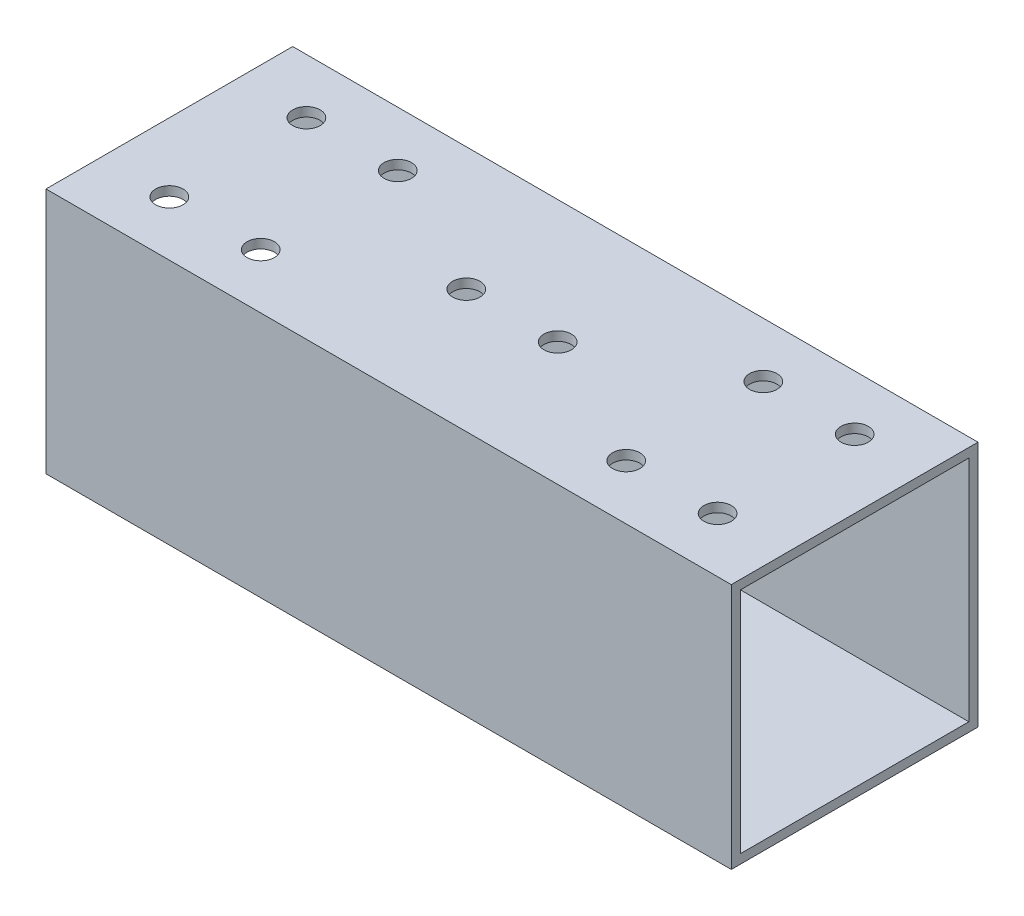
SolidWorks part; units mm, degrees
material "Plain Carbon Steel"
ref_plane "Front Plane" through (0, 0, 0) normal (0, 0, 1) x (1, 0, 0)
ref_plane "Top Plane" through (0, 0, 0) normal (0, 1, 0) x (1, 0, 0)
ref_plane "Right Plane" through (0, 0, 0) normal (1, 0, 0) x (0, 0, -1)
sketch "Sketch1" plane through (0, 0, 0) normal (1, 0, 0) x (0, 0, -1)
  line L1 (27, -27) -> (-27, -27)
  line L2 (27, -27) -> (27, 27)
  line L3 (27, 27) -> (-27, 27)
  line L4 (-27, -27) -> (-27, 27)
  line L5 (27, -27) -> (-27, 27) construction
  line L6 (27, 27) -> (-27, -27) construction
  line L11 (23.1777, -23.1777) -> (-23.1777, 23.1777) construction
  line L12 (23.1777, 23.1777) -> (-23.1777, -23.1777) construction
  line L13 (-25, -25) -> (25, -25)
  line L14 (-25, -25) -> (-25, 25)
  line L15 (-25, 25) -> (25, 25)
  line L16 (25, -25) -> (25, 25)
  line L17 (-25, -25) -> (25, 25) construction
  line L18 (-25, 25) -> (25, -25) construction
  point P0 (0, 0)
  point P6 (0, 0)
  point P11 (0, 0)
  dimension "D1" = 54
  dimension "D2" = 54
  dimension "D3" = 50
  dimension "D4" = 50
extrude "Boss-Extrude1" add sketch "Sketch1" along normal mid plane 150
sketch "Sketch2" plane through (0, 27, 0) normal (0, 1, 0) x (1, 0, 0)
  line L0 (0, -29.7) -> (0, 29.7) construction
  circle A0 centre (-60, 15) radius 3
  circle A1 centre (-60, -15) radius 3
  circle A2 centre (60, 15) radius 3
  circle A3 centre (60, -15) radius 3
  circle A4 centre (-40, -15) radius 3
  circle A5 centre (-40, 15) radius 3
  circle A6 centre (40, -15) radius 3
  circle A7 centre (40, 15) radius 3
  dimension "D1" = 6
  dimension "D2" = 6
  dimension "D3" = 6
  dimension "D4" = 6
  dimension "D5" = 60
  dimension "D7" = 60
  dimension "D9" = 15
  dimension "D10" = 15
  dimension "D11" = 15
  dimension "D12" = 15
  dimension "D13" = 6
  dimension "D14" = 6
  dimension "D15" = 20
  dimension "D16" = 20
  dimension "D17" = 15
  dimension "D18" = 15
  dimension "D6" = 60
  dimension "D8" = 60
extrude "Cut-Extrude1" cut sketch "Sketch2" against normal blind 25
sketch "Sketch3" plane through (0, 27, 0) normal (0, 1, 0) x (1, 0, 0)
  circle A0 centre (-10, 0) radius 3
  circle A1 centre (10, 0) radius 3
  dimension "D1" = 6
  dimension "D2" = 6
  dimension "D3" = 20
  dimension "D4" = 10
extrude "Cut-Extrude2" cut sketch "Sketch3" against normal blind 25
